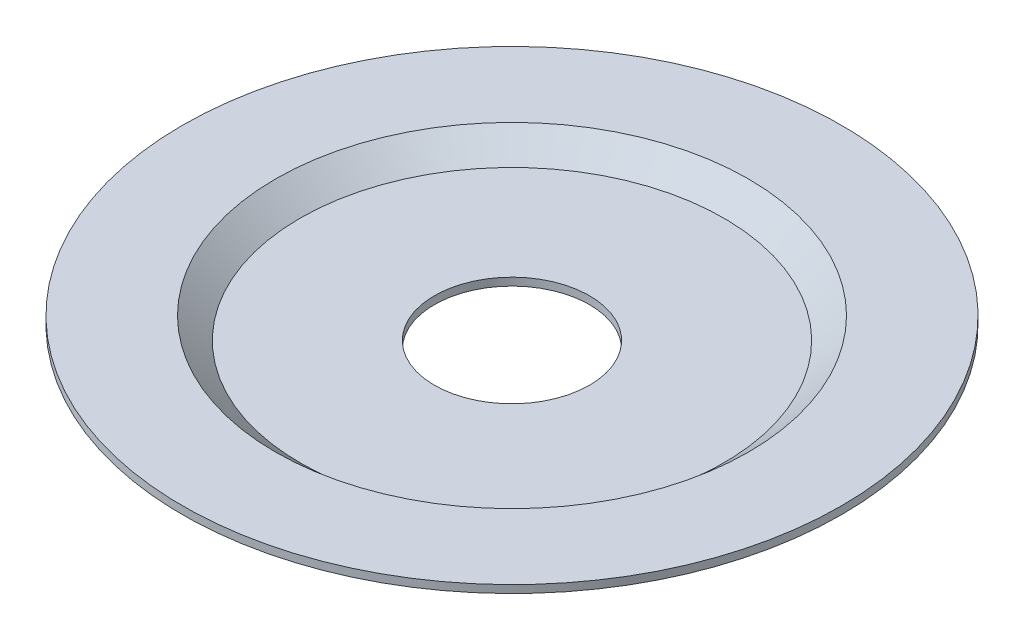
SolidWorks part; units mm, degrees
material "ABS PC"
ref_plane "Front Plane" through (0, 0, 0) normal (0, 0, 1) x (1, 0, 0)
ref_plane "Top Plane" through (0, 0, 0) normal (0, 1, 0) x (1, 0, 0)
ref_plane "Right Plane" through (0, 0, 0) normal (1, 0, 0) x (0, 0, -1)
sketch "Sketch6" plane through (0, 0, 0) normal (0, 0, 1) x (1, 0, 0)
  line L0 (0.0119, 83.7697) -> (0.0119, 1.4242) construction
  line L1 (85, 0) -> (61.0119, 0)
  line L2 (0.0119, -7.5758) -> (55.4119, -7.5758)
  line L3 (55.4119, -7.5758) -> (61.7651, -2)
  line L4 (61.7651, -2) -> (85, -2)
  line L5 (85, -2) -> (85, 0)
  line L6 (61.0119, 0) -> (54.6588, -5.5758)
  line L7 (0.0119, -7.5758) -> (0.0119, -80.9214) construction
  line L8 (54.6588, -5.5758) -> (0.0119, -5.5758)
  line L9 (0.0119, -5.5758) -> (0.0119, -7.5758)
  point P4 (58.5885, -4.7879)
  dimension "D1" = 55.4
  dimension "D2" = 85
  dimension "D3" = 2
  dimension "D4" = 9
  dimension "D5" = 61
  dimension "D6" = 2
  dimension "D7" = 2
revolve "Revolve2" add sketch "Sketch6" angle 360 about L0
sketch "Sketch7" plane through (0, -7.5758, 0) normal (0, -1, 0) x (1, 0, 0)
  circle A0 centre (0, 0) radius 20
  dimension "D1" = 40
extrude "Cut-Extrude1" cut sketch "Sketch7" against normal through all
